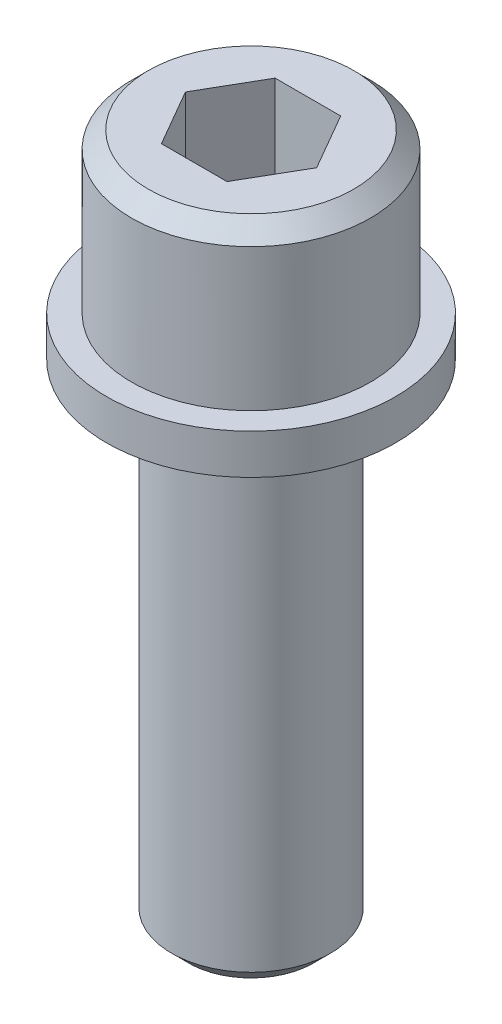
SolidWorks part; units mm, degrees
ref_plane "Front Plane" through (0, 0, 0) normal (0, 0, 1) x (1, 0, 0)
ref_plane "Top Plane" through (0, 0, 0) normal (0, 1, 0) x (1, 0, 0)
ref_plane "Right Plane" through (0, 0, 0) normal (1, 0, 0) x (0, 0, -1)
sketch "Sketch1" plane through (0, 0, 0) normal (0, 0, 1) x (1, 0, 0)
  line L0 (0, 0) -> (0, 41.3)
  line L1 (0, 41.3) -> (7.15, 41.3)
  line L2 (7.15, 41.3) -> (7.15, 31.8)
  line L3 (7.15, 31.8) -> (8.65, 31.8)
  line L4 (8.65, 31.8) -> (8.65, 29.4)
  line L5 (8.65, 29.4) -> (4.75, 29.4)
  line L6 (4.75, 29.4) -> (4.75, 0)
  line L7 (4.75, 0) -> (0, 0)
  dimension "D1" = 4.75
  dimension "D2" = 7.15
  dimension "D3" = 2.4
  dimension "D4" = 8.65
  dimension "D5" = 9.5
  dimension "D6" = 41.3
revolve "Revolve1" add sketch "Sketch1" angle 360 about L0
sketch "Sketch2" plane through (0, 41.3, 0) normal (0, 1, 0) x (1, 0, 0)
  line L1 (3.926, 0) -> (1.963, 3.4)
  line L2 (1.963, 3.4) -> (-1.963, 3.4)
  line L3 (-1.963, 3.4) -> (-3.926, 0)
  line L4 (-3.926, 0) -> (-1.963, -3.4)
  line L5 (-1.963, -3.4) -> (1.963, -3.4)
  line L6 (1.963, -3.4) -> (3.926, 0)
  circle A0 centre (0, 0) radius 3.4 construction
  dimension "D1" = 6.8
extrude "Cut-Extrude1" cut sketch "Sketch2" against normal blind 6.4
chamfer "Chamfer1" distance 1 angle 45 2 edges at (0, 0, -4.75) (0, 41.3, -7.15)
